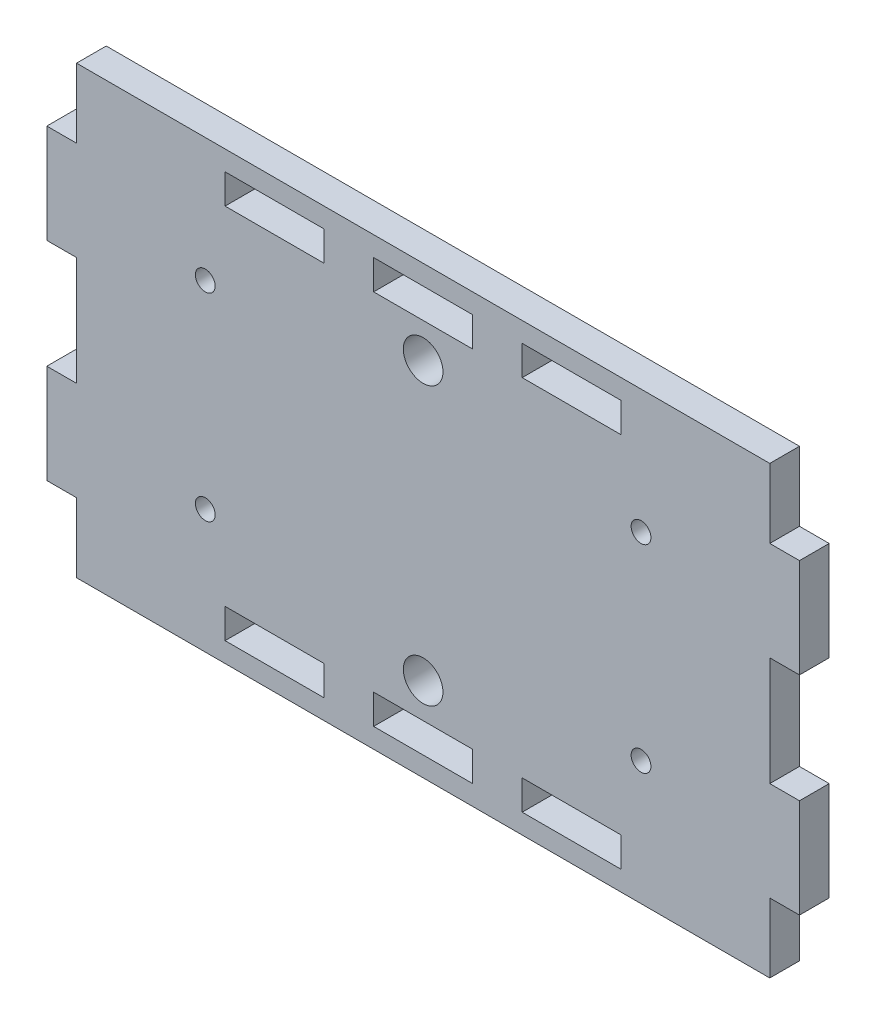
SolidWorks part; units mm, degrees
ref_plane "前视基准面" through (0, 0, 0) normal (0, 0, 1) x (1, 0, 0)
ref_plane "上视基准面" through (0, 0, 0) normal (0, 1, 0) x (1, 0, 0)
ref_plane "右视基准面" through (0, 0, 0) normal (1, 0, 0) x (0, 0, -1)
sketch "草图1" plane through (0, 0, 0) normal (0, 0, 1) x (1, 0, 0)
  line L0 (0, -55) -> (0, 55) construction
  line L1 (-22, 10) -> (22, 10) construction
  line L2 (-22, 10) -> (-22, -10) construction
  line L3 (-22, -10) -> (22, -10) construction
  line L4 (22, 10) -> (22, -10) construction
  line L5 (-22, 10) -> (22, -10) construction
  line L6 (-22, -10) -> (22, 10) construction
  line L8 (-35, 17.5) -> (-35, 15.5)
  line L10 (35, 17.5) -> (35, 15.5)
  line L11 (-35, 17.5) -> (35, -17.5) construction
  line L12 (-35, -17.5) -> (35, 17.5) construction
  line L13 (55, 0) -> (-55, 0) construction
  line L14 (-5, 17.5) -> (-5, 20.5)
  line L15 (-20, 17.5) -> (-10, 17.5)
  line L16 (-20, 17.5) -> (-20, 20.5)
  line L17 (-20, 20.5) -> (-10, 20.5)
  line L18 (-10, 17.5) -> (-10, 20.5)
  line L19 (-5, 17.5) -> (5, 17.5)
  line L20 (5, 17.5) -> (5, 20.5)
  line L21 (-5, 20.5) -> (5, 20.5)
  line L22 (10, 17.5) -> (10, 20.5)
  line L23 (10, 17.5) -> (20, 17.5)
  line L24 (20, 17.5) -> (20, 20.5)
  line L25 (10, 20.5) -> (20, 20.5)
  line L26 (-35, 17.5) -> (-35, 22.5)
  line L27 (-35, 22.5) -> (35, 22.5)
  line L28 (35, 22.5) -> (35, 17.5)
  line L29 (35, -5.5) -> (38, -5.5)
  line L30 (35, 15.5) -> (38, 15.5)
  line L32 (35, 5.5) -> (38, 5.5)
  line L33 (38, 15.5) -> (38, 5.5)
  line L34 (38, -15.5) -> (38, -5.5)
  line L35 (35, -15.5) -> (38, -15.5)
  line L38 (-35, -15.5) -> (-38, -15.5)
  line L39 (-38, -15.5) -> (-38, -5.5)
  line L40 (-35, -5.5) -> (-38, -5.5)
  line L41 (-35, 5.5) -> (-38, 5.5)
  line L42 (-38, 15.5) -> (-38, 5.5)
  line L43 (-35, 15.5) -> (-38, 15.5)
  line L45 (10, -17.5) -> (20, -17.5)
  line L46 (20, -17.5) -> (20, -20.5)
  line L47 (10, -20.5) -> (20, -20.5)
  line L48 (10, -17.5) -> (10, -20.5)
  line L49 (-5, -17.5) -> (5, -17.5)
  line L50 (5, -17.5) -> (5, -20.5)
  line L51 (-5, -20.5) -> (5, -20.5)
  line L52 (-5, -17.5) -> (-5, -20.5)
  line L53 (-20, -20.5) -> (-10, -20.5)
  line L54 (-10, -17.5) -> (-10, -20.5)
  line L55 (-20, -17.5) -> (-10, -17.5)
  line L56 (-20, -17.5) -> (-20, -20.5)
  line L57 (-35, -17.5) -> (-35, -22.5)
  line L58 (-35, -22.5) -> (35, -22.5)
  line L59 (35, -22.5) -> (35, -17.5)
  line L60 (-35, 5.5) -> (-35, -5.5)
  line L61 (-35, -15.5) -> (-35, -17.5)
  line L62 (35, -15.5) -> (35, -17.5)
  line L63 (35, 5.5) -> (35, -5.5)
  circle A0 centre (0, 14) radius 2
  circle A1 centre (0, -14) radius 2
  circle A2 centre (22, 10) radius 1
  circle A3 centre (22, -10) radius 1
  circle A4 centre (-22, -10) radius 1
  circle A5 centre (-22, 10) radius 1
  point P0 (0, 0)
  point P5 (0, 0)
  dimension "D5" = 10
  dimension "D1" = 44
  dimension "D2" = 20
  dimension "D3" = 70
  dimension "D4" = 35
  dimension "D6" = 10
  dimension "D7" = 3
  dimension "D8" = 15
  dimension "D10" = 3
  dimension "D11" = 7
  dimension "D9" = 3
extrude "凸台-拉伸1" add sketch "草图1" along normal blind 3
